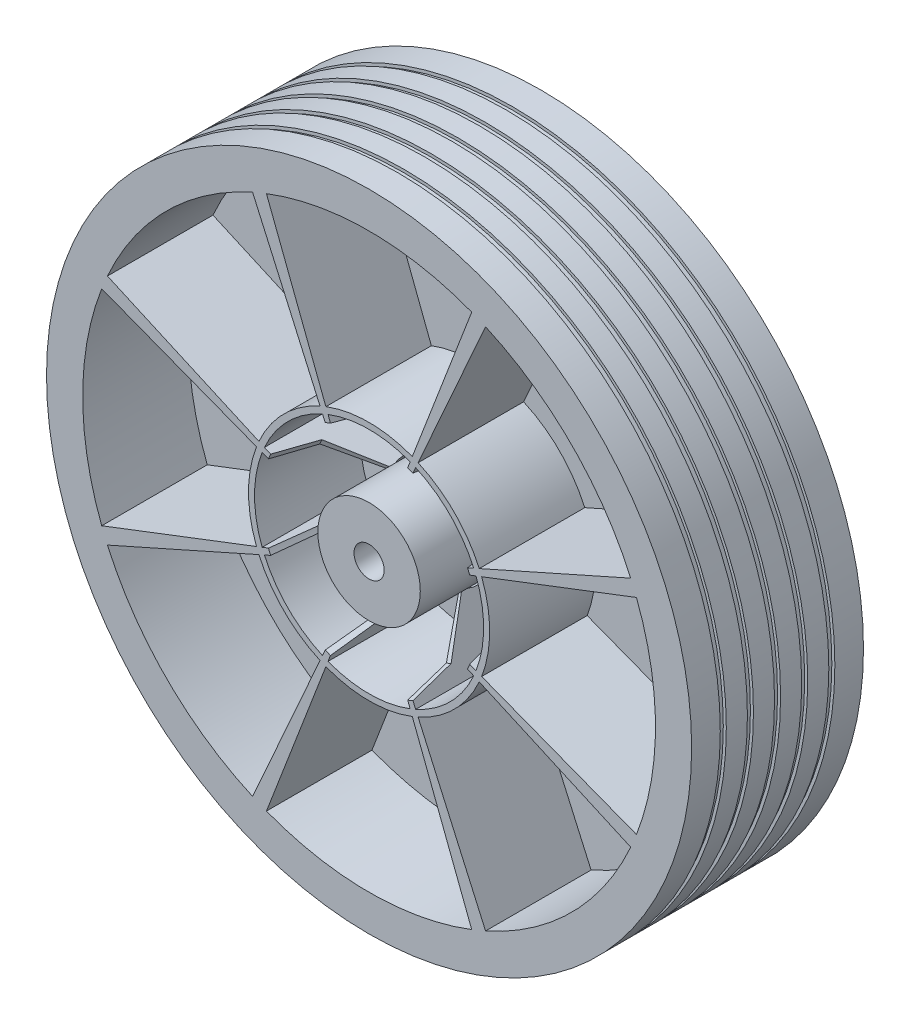
SolidWorks part; units mm, degrees
material "PF"
ref_plane "Front Plane" through (0, 0, 0) normal (0, 0, 1) x (1, 0, 0)
ref_plane "Top Plane" through (0, 0, 0) normal (0, 1, 0) x (1, 0, 0)
ref_plane "Right Plane" through (0, 0, 0) normal (1, 0, 0) x (0, 0, -1)
sketch "Sketch1" plane through (0, 0, 0) normal (0, 0, 1) x (1, 0, 0)
  circle A0 centre (0, 0) radius 107
  dimension "D1" = 214
extrude "Boss-Extrude1" add sketch "Sketch1" along normal blind 57
sketch "Sketch3" plane through (0, 0, 0) normal (1, 0, 0) x (0, 0, -1)
  line L0 (0, 0) -> (-87.8855, 0) construction
  line L1 (-57, 107) -> (-57, -107) construction
  line L2 (-47.5, 108.6364) -> (-45.5, 108.6364)
  line L3 (-47.5, 108.6364) -> (-47.5, 106)
  line L4 (-47.5, 106) -> (-45.5, 106)
  line L5 (-45.5, 108.6364) -> (-45.5, 106)
  line L6 (0, 107) -> (-57, 107) construction
  line L7 (-36.5, 108.6364) -> (-36.5, 106)
  line L8 (-38.5, 106) -> (-36.5, 106)
  line L9 (-38.5, 108.6364) -> (-36.5, 108.6364)
  line L10 (-38.5, 108.6364) -> (-38.5, 106)
  line L11 (-27.5, 108.6364) -> (-27.5, 106)
  line L12 (-29.5, 106) -> (-27.5, 106)
  line L13 (-29.5, 108.6364) -> (-27.5, 108.6364)
  line L14 (-29.5, 108.6364) -> (-29.5, 106)
  line L15 (-18.5, 108.6364) -> (-18.5, 106)
  line L16 (-20.5, 106) -> (-18.5, 106)
  line L17 (-20.5, 108.6364) -> (-18.5, 108.6364)
  line L18 (-20.5, 108.6364) -> (-20.5, 106)
  line L19 (-9.5, 108.6364) -> (-9.5, 106)
  line L20 (-11.5, 106) -> (-9.5, 106)
  line L21 (-11.5, 108.6364) -> (-9.5, 108.6364)
  line L22 (-11.5, 108.6364) -> (-11.5, 106)
  dimension "D1" = 9.5
  dimension "D2" = 2
  dimension "D3" = 1
  dimension "D4" = 5
revolve "Cut-Revolve3" cut sketch "Sketch3" angle 360 about L0
sketch "Sketch6" plane through (0, 0, 0) normal (1, 0, 0) x (0, 0, -1)
  line L0 (20.4822, 0) -> (-84.4177, 0) construction
  line L1 (5, 95) -> (5, 25)
  line L2 (5, 25) -> (-5, 25)
  line L3 (-5, 25) -> (-10, 95)
  line L4 (-10, 95) -> (5, 95)
  line L5 (0, 107) -> (-9.5, 107) construction
  line L6 (0, -107) -> (0, 107) construction
  dimension "D1" = 50
  dimension "D2" = 12
  dimension "D3" = 15
  dimension "D4" = 10
  dimension "D5" = 5
revolve "Cut-Revolve4" cut sketch "Sketch6" angle 360 about L0
sketch "Sketch7" plane through (0, 0, 0) normal (0, 0, -1) x (-1, 0, 0)
  circle A0 centre (0, 0) radius 25
extrude "Boss-Extrude2" add sketch "Sketch7" along normal blind 20
sketch "Sketch8" plane through (0, 0, 57) normal (0, 0, 1) x (1, 0, 0)
  line L0 (0, 0) -> (0, 112.9191) construction
  line L1 (14.3347, 37.3432) -> (34.045, 88.6901)
  line L2 (-14.3347, 37.3432) -> (-34.045, 88.6901)
  line L3 (-13.618, 35.4761) -> (-6.2714, 16.3377)
  line L4 (13.618, 35.4761) -> (6.2714, 16.3377)
  arc A0 (34.045, 88.6901) -> (-34.045, 88.6901) centre (0, 0) ccw
  arc A1 (14.3347, 37.3432) -> (-14.3347, 37.3432) centre (0, 0) ccw
  arc A2 (13.618, 35.4761) -> (-13.618, 35.4761) centre (0, 0) ccw
  arc A3 (6.2714, 16.3377) -> (-6.2714, 16.3377) centre (0, 0) ccw
  point P5 (0, 0)
  dimension "D1" = 190
  dimension "D4" = 80
  dimension "D7" = 76
  dimension "D8" = 35
  dimension "D11" = 42
  dimension "D2" = 21
  dimension "D3" = 21
  dimension "D5" = 55
  dimension "D6" = 55
  dimension "D9" = 20.5
  dimension "D10" = 20.5
  dimension "D12" = 21
extrude "Cut-Extrude1" cut sketch "Sketch8" against normal blind 35
pattern_circular "CirPattern5" count 8 over 360 about axis through (0, 0, 0) along (0, 0, 1) of "Cut-Extrude1"
sketch "Sketch10" plane through (0, 0, 0) normal (1, 0, 0) x (0, 0, -1)
  line L0 (-58, 35.987) -> (-43, 32.4761)
  line L1 (-43, 32.4761) -> (-33, 16.987)
  line L2 (-33, 16.987) -> (-58, 16.987)
  line L3 (-58, 16.987) -> (-58, 35.987)
  line L5 (-22, 15.987) -> (-57, 15.987) construction
  line L7 (-57, 16.2695) -> (-57, 38.64) construction
  line L8 (-22, 35.4761) -> (-57, 35.4761) construction
  line L9 (0, 0) -> (-96.5585, 0) construction
  point P6 (-57, 27.4547)
  dimension "D1" = 19
  dimension "D2" = 1
  dimension "D3" = 15
  dimension "D4" = 25
  dimension "D5" = 1
  dimension "D6" = 3
revolve "Cut-Revolve5" cut sketch "Sketch10" angle 360 about L9
sketch "Sketch11" plane through (0, 0, 57) normal (0, 0, 1) x (1, 0, 0)
  circle A0 centre (0, 0) radius 5
  dimension "D1" = 10
extrude "Cut-Extrude2" cut sketch "Sketch11" against normal through all
